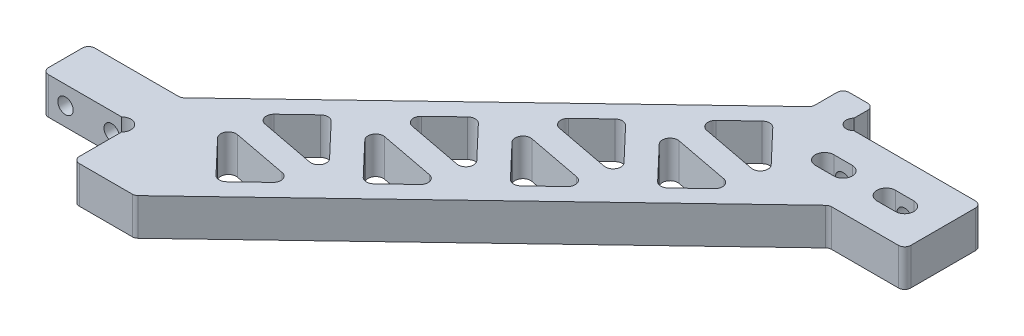
SolidWorks part; units mm, degrees
ref_plane "正面" through (0, 0, 0) normal (0, 0, 1) x (1, 0, 0)
ref_plane "平面" through (0, 0, 0) normal (0, 1, 0) x (1, 0, 0)
ref_plane "右側面" through (0, 0, 0) normal (1, 0, 0) x (0, 0, -1)
sketch "ｽｹｯﾁ1" plane through (0, 0, 0) normal (0, 1, 0) x (1, 0, 0)
  line L1 (0, 0) -> (65, 0) construction
  line L2 (0, 0) -> (0, 62.5) construction
  line L3 (0, 62.5) -> (65, 62.5) construction
  line L4 (65, 0) -> (65, 62.5) construction
  line L5 (7.5, -10) -> (-7.5, -10) construction
  line L6 (7.5, -10) -> (7.5, 0) construction
  line L7 (7.5, 0) -> (-7.5, 0) construction
  line L8 (-7.5, -10) -> (-7.5, 0) construction
  line L11 (7.5, -10) -> (7.5, 0)
  line L12 (7.5, 0) -> (-7.5, 0)
  line L13 (-7.5, 0) -> (-7.5, 7.5)
  line L18 (7.5, 0) -> (6.4393, -1.0607) construction
  line L19 (60, 57.5) -> (60, 62.5)
  line L20 (60, 62.5) -> (65, 62.5)
  line L21 (65, 62.5) -> (65, 57.5)
  line L23 (65, 57.5) -> (65.8839, 58.3839) construction
  line L24 (-7.5, 7.5) -> (7.5, 7.5)
  line L25 (-5, 0) -> (-2.5, 0) construction
  line L26 (-5, 0) -> (-5, 7.5) construction
  line L27 (-5, 7.5) -> (-2.5, 7.5) construction
  line L28 (-2.5, 0) -> (-2.5, 7.5) construction
  line L29 (2.5, 0) -> (5, 0) construction
  line L30 (2.5, 0) -> (2.5, 7.5) construction
  line L31 (2.5, 7.5) -> (5, 7.5) construction
  line L32 (5, 0) -> (5, 7.5) construction
  line L33 (7.5, 7.5) -> (60, 57.5)
  line L34 (65, 57.5) -> (87.5, 57.5)
  line L35 (87.5, 57.5) -> (87.5, 45)
  line L38 (87.5, 45) -> (75.25, 45)
  line L39 (68.75, 57.5) -> (71.25, 57.5) construction
  line L40 (68.75, 57.5) -> (68.75, 52.5) construction
  line L41 (68.75, 52.5) -> (71.25, 52.5) construction
  line L42 (71.25, 57.5) -> (71.25, 52.5) construction
  line L43 (81.25, 57.5) -> (78.75, 57.5) construction
  line L44 (81.25, 57.5) -> (81.25, 52.5) construction
  line L45 (81.25, 52.5) -> (78.75, 52.5) construction
  line L46 (78.75, 57.5) -> (78.75, 52.5) construction
  line L47 (75.25, 45) -> (17.5, -10)
  line L48 (17.5, -10) -> (7.5, -10)
  line L49 (68.5, 51) -> (71.5, 51) construction
  line L50 (68.5, 52.5) -> (71.5, 52.5)
  line L51 (68.5, 49.5) -> (71.5, 49.5)
  line L52 (78.5, 51) -> (81.5, 51) construction
  line L53 (78.5, 52.5) -> (81.5, 52.5)
  line L54 (78.5, 49.5) -> (81.5, 49.5)
  circle A0 centre (6.4393, -1.0607) radius 1.5
  circle A1 centre (65.8839, 58.3839) radius 1.25
  arc A2 (68.5, 52.5) -> (68.5, 49.5) centre (68.5, 51) ccw
  arc A3 (71.5, 49.5) -> (71.5, 52.5) centre (71.5, 51) ccw
  arc A4 (78.5, 52.5) -> (78.5, 49.5) centre (78.5, 51) ccw
  arc A5 (81.5, 49.5) -> (81.5, 52.5) centre (81.5, 51) ccw
  point P9 (0, 0)
  point P32 (3.75, 7.5)
  point P33 (-3.75, 7.5)
  point P40 (70, 57.5)
  point P41 (70, 52.5)
  point P42 (80, 52.5)
  point P46 (70, 51)
  point P51 (0, 0)
  point P52 (70, 52.5)
  point P53 (0, 0)
  point P54 (70.2267, 81.002)
  point P55 (0, 0)
  point P56 (70, 82.5728)
  point P57 (0, 0)
  point P58 (48.3747, 81.5)
  point P61 (80, 51)
  point P66 (80, 52.5)
  point P67 (77.8536, 83)
  dimension "D10" = 3
  dimension "D14" = 2.5
  dimension "D13" = 45
  dimension "D25" = 1.5
  dimension "D1" = 62.5
  dimension "D2" = 65
  dimension "D3" = 15
  dimension "D4" = 10
  dimension "D5" = 5
  dimension "D6" = 22.5
  dimension "D7" = 7.5
  dimension "D8" = 12.5
  dimension "D9" = 5
  dimension "D11" = 45
  dimension "D12" = 5
  dimension "D15" = 2.5
  dimension "D16" = 2.5
  dimension "D17" = 7.5
  dimension "D18" = 7.5
  dimension "D19" = 3.75
  dimension "D20" = 2.5
  dimension "D21" = 10
  dimension "D22" = 5
  dimension "D23" = 5
  dimension "D24" = 10
  dimension "D26" = 3
extrude "ﾎﾞｽ - 押し出し1" add sketch "ｽｹｯﾁ1" along normal mid plane 6
fillet "ﾌｨﾚｯﾄ2" radius 1 11 edges at (-7.5, 0, 0) (65, 0, -62.5) (60, 0, -62.5) (60, 0, -57.5) (7.5, 0, -7.5) (-7.5, 0, -7.5) (7.5, 0, 10) (17.5, 0, 10) (75.25, 0, -45) (87.5, 0, -45) (87.5, 0, -57.5)
sketch "ｽｹｯﾁ2" plane through (0, 3, 0) normal (0, 1, 0) x (1, 0, 0)
  line L0 (7.7897, 7.7759) -> (21.2855, -6.3948) construction
  line L1 (59.6897, 57.2044) -> (73.1855, 43.0338) construction
  line L13 (58.8621, 52.2734) -> (52.3448, 46.0665)
  line L21 (52.3448, 46.0665) -> (67.5303, 43.1717)
  line L49 (67.5303, 43.1717) -> (58.8621, 52.2734)
  line L71 (50.1719, 42.6161) -> (65.3574, 39.7213)
  line L72 (65.3574, 39.7213) -> (58.8402, 33.5145)
  line L73 (58.8402, 33.5145) -> (50.1719, 42.6161)
  line L74 (14.5376, 0.6905) -> (66.4376, 50.1191) construction
  line L75 (46.6197, 40.614) -> (40.1025, 34.4071)
  line L76 (55.288, 31.5123) -> (46.6197, 40.614)
  line L77 (40.1025, 34.4071) -> (55.288, 31.5123)
  line L78 (37.9296, 30.9567) -> (53.1151, 28.062)
  line L79 (65, 59.2678) -> (65, 61.5)
  line L80 (64, 62.5) -> (61, 62.5)
  line L81 (60, 61.5) -> (60, 57.9286)
  line L162 (59.6897, 57.2044) -> (7.7897, 7.7759)
  line L163 (7.1, 7.5) -> (-6.5, 7.5)
  line L164 (-7.5, 6.5) -> (-7.5, 1)
  line L166 (-6.5, 0) -> (5.3787, 0)
  line L167 (7.5, -2.1213) -> (7.5, -9)
  line L169 (8.5, -10) -> (17.1, -10)
  line L170 (17.7897, -9.7241) -> (74.9603, 44.7241)
  line L172 (75.65, 45) -> (86.5, 45)
  line L173 (87.5, 46) -> (87.5, 56.5)
  line L179 (86.5, 57.5) -> (66.7678, 57.5)
  line L182 (65, 59.2678) -> (65, 61.5) construction
  line L185 (64, 62.5) -> (61, 62.5) construction
  line L188 (60, 61.5) -> (60, 57.9286) construction
  line L189 (59.6897, 57.2044) -> (7.7897, 7.7759) construction
  line L190 (7.1, 7.5) -> (-6.5, 7.5) construction
  line L191 (-7.5, 6.5) -> (-7.5, 1) construction
  line L193 (-6.5, 0) -> (5.3787, 0) construction
  line L194 (7.5, -2.1213) -> (7.5, -9) construction
  line L195 (8.5, -10) -> (17.1, -10) construction
  line L196 (17.7897, -9.7241) -> (74.9603, 44.7241) construction
  line L197 (75.65, 45) -> (86.5, 45) construction
  line L198 (87.5, 46) -> (87.5, 56.5) construction
  line L199 (86.5, 57.5) -> (66.7678, 57.5) construction
  line L200 (46.5978, 21.8551) -> (37.9296, 30.9567)
  line L201 (53.1151, 28.062) -> (46.5978, 21.8551)
  line L202 (34.3773, 28.9546) -> (27.8601, 22.7477)
  line L203 (43.0456, 19.8529) -> (34.3773, 28.9546)
  line L204 (27.8601, 22.7477) -> (43.0456, 19.8529)
  line L205 (25.6872, 19.2973) -> (40.8727, 16.4026)
  line L206 (34.3554, 10.1957) -> (25.6872, 19.2973)
  line L207 (40.8727, 16.4026) -> (34.3554, 10.1957)
  line L210 (22.135, 17.2952) -> (15.6177, 11.0883)
  line L212 (30.8032, 8.1935) -> (22.135, 17.2952)
  line L216 (15.6177, 11.0883) -> (30.8032, 8.1935)
  line L217 (13.4448, 7.6379) -> (28.6303, 4.7432)
  line L218 (22.1131, -1.4637) -> (13.4448, 7.6379)
  line L219 (28.6303, 4.7432) -> (22.1131, -1.4637)
  line L220 (28.6303, 4.7432) -> (34.3554, 10.1957) construction
  arc A14 (65, 61.5) -> (64, 62.5) centre (64, 61.5) ccw
  arc A15 (61, 62.5) -> (60, 61.5) centre (61, 61.5) ccw
  arc A16 (59.6897, 57.2044) -> (60, 57.9286) centre (59, 57.9286) ccw
  arc A20 (7.1, 7.5) -> (7.7897, 7.7759) centre (7.1, 8.5) ccw
  arc A22 (-6.5, 7.5) -> (-7.5, 6.5) centre (-6.5, 6.5) ccw
  arc A47 (-7.5, 1) -> (-6.5, 0) centre (-6.5, 1) ccw
  arc A48 (7.5, -2.1213) -> (5.3787, 0) centre (6.4393, -1.0607) ccw
  arc A49 (7.5, -9) -> (8.5, -10) centre (8.5, -9) ccw
  arc A50 (17.1, -10) -> (17.7897, -9.7241) centre (17.1, -9) ccw
  arc A51 (75.65, 45) -> (74.9603, 44.7241) centre (75.65, 44) ccw
  arc A52 (86.5, 45) -> (87.5, 46) centre (86.5, 46) ccw
  arc A53 (87.5, 56.5) -> (86.5, 57.5) centre (86.5, 56.5) ccw
  arc A54 (65, 59.2678) -> (66.7678, 57.5) centre (65.8839, 58.3839) ccw
  arc A68 (65, 61.5) -> (64, 62.5) centre (64, 61.5) ccw construction
  arc A69 (61, 62.5) -> (60, 61.5) centre (61, 61.5) ccw construction
  arc A70 (59.6897, 57.2044) -> (60, 57.9286) centre (59, 57.9286) ccw construction
  arc A71 (7.1, 7.5) -> (7.7897, 7.7759) centre (7.1, 8.5) ccw construction
  arc A72 (-6.5, 7.5) -> (-7.5, 6.5) centre (-6.5, 6.5) ccw construction
  arc A73 (-7.5, 1) -> (-6.5, 0) centre (-6.5, 1) ccw construction
  arc A74 (7.5, -2.1213) -> (5.3787, 0) centre (6.4393, -1.0607) ccw construction
  arc A75 (7.5, -9) -> (8.5, -10) centre (8.5, -9) ccw construction
  arc A76 (17.1, -10) -> (17.7897, -9.7241) centre (17.1, -9) ccw construction
  arc A77 (75.65, 45) -> (74.9603, 44.7241) centre (75.65, 44) ccw construction
  arc A78 (86.5, 45) -> (87.5, 46) centre (86.5, 46) ccw construction
  arc A79 (87.5, 56.5) -> (86.5, 57.5) centre (86.5, 56.5) ccw construction
  arc A80 (65, 59.2678) -> (66.7678, 57.5) centre (65.8839, 58.3839) ccw construction
  point P42 (31.4929, 7.4694)
  point P66 (50.0805, 28.9041)
  point P68 (51.7022, 28.5098)
  dimension "D2" = 3
  dimension "D3" = 4
  dimension "D4" = 4
  dimension "D5" = 3
  dimension "D7" = 4
  dimension "D8" = 4
  dimension "D9" = 9
  dimension "D6" = 4
  dimension "D1" = 0
extrude "ｶｯﾄ - 押し出し1" cut sketch "ｽｹｯﾁ2" against normal blind 6
fillet "ﾌｨﾚｯﾄ3" radius 1.25 24 edges at (58.8621, 0, -52.2734) (28.6303, 0, -4.7432) (22.1131, 0, 1.4637) (13.4448, 0, -7.6379) (40.8727, 0, -16.4026) (34.3554, 0, -10.1957) (25.6872, 0, -19.2973) (15.6177, 0, -11.0883) (22.135, 0, -17.2952) (30.8032, 0, -8.1935) (53.1151, 0, -28.062) (46.5978, 0, -21.8551) (37.9296, 0, -30.9567) (27.8601, 0, -22.7477) (34.3773, 0, -28.9546) (43.0456, 0, -19.8529) (58.8402, 0, -33.5145) (50.1719, 0, -42.6161) (40.1025, 0, -34.4071) (46.6197, 0, -40.614) (55.288, 0, -31.5123) (65.3574, 0, -39.7213) (52.3448, 0, -46.0665) (67.5303, 0, -43.1717)
sketch "ｽｹｯﾁ6" plane through (0, 0, 0) normal (0, 0, 1) x (1, 0, 0)
  line L0 (-7.5, 0) -> (0, 0) construction
  line L1 (-7.5, -3) -> (-7.5, 3) construction
  line L2 (0, 0) -> (0, 3) construction
  line L3 (5.3787, 3) -> (-6.5, 3) construction
  circle A0 centre (-3.75, 0) radius 1.25
  circle A1 centre (3.75, 0) radius 1.25
  point P7 (0, 3)
  dimension "D1" = 2.5
  dimension "D2" = 3.75
extrude "ｶｯﾄ - 押し出し4" cut sketch "ｽｹｯﾁ6" against normal through all
sketch "ｽｹｯﾁ7" plane through (0, 0, -57.5) normal (0, 0, -1) x (-1, 0, 0)
  line L0 (-65, 0) -> (-70, 0) construction
  line L1 (-75, 3) -> (-75, -3) construction
  line L2 (-66.7678, 3) -> (-86.5, 3) construction
  line L3 (-66.7678, -3) -> (-86.5, -3) construction
  line L4 (-64, 3) -> (-65, 3)
  line L5 (-65, 3) -> (-65, -3)
  line L6 (-65, -3) -> (-64, -3)
  line L7 (-64, -3) -> (-64, 3)
  line L8 (-64, 3) -> (-65, 3) construction
  line L9 (-65, 3) -> (-65, -3) construction
  line L10 (-65, -3) -> (-64, -3) construction
  line L11 (-64, -3) -> (-64, 3) construction
  circle A0 centre (-70, 0) radius 1.25
  circle A1 centre (-80, 0) radius 1.25
  dimension "D3" = 2.5
  dimension "D2" = 5
  dimension "D4" = 5
  dimension "D1" = 0
extrude "ｶｯﾄ - 押し出し5" cut sketch "ｽｹｯﾁ7" against normal up to surface (8 mm away) up to face at (80, 0, -49.5)
